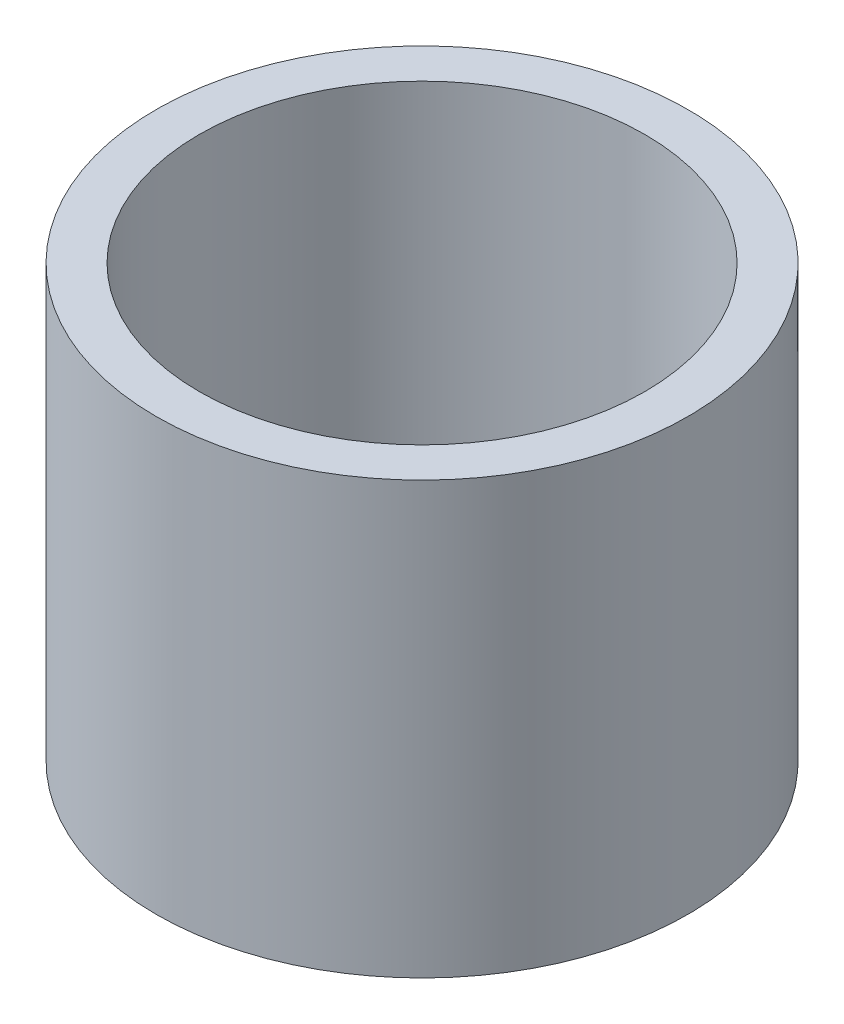
SolidWorks part; units mm, degrees
ref_plane "Front Plane" through (0, 0, 0) normal (0, 0, 1) x (1, 0, 0)
ref_plane "Top Plane" through (0, 0, 0) normal (0, 1, 0) x (1, 0, 0)
ref_plane "Right Plane" through (0, 0, 0) normal (1, 0, 0) x (0, 0, -1)
sketch "Sketch1" plane through (0, 0, 0) normal (0, 1, 0) x (1, 0, 0)
  circle A0 centre (0, 0) radius 15.5
  circle A1 centre (0, 0) radius 18.5
  dimension "D1" = 31
  dimension "D2" = 37
extrude "Boss-Extrude1" add sketch "Sketch1" along normal blind 30 contours A1 A0
